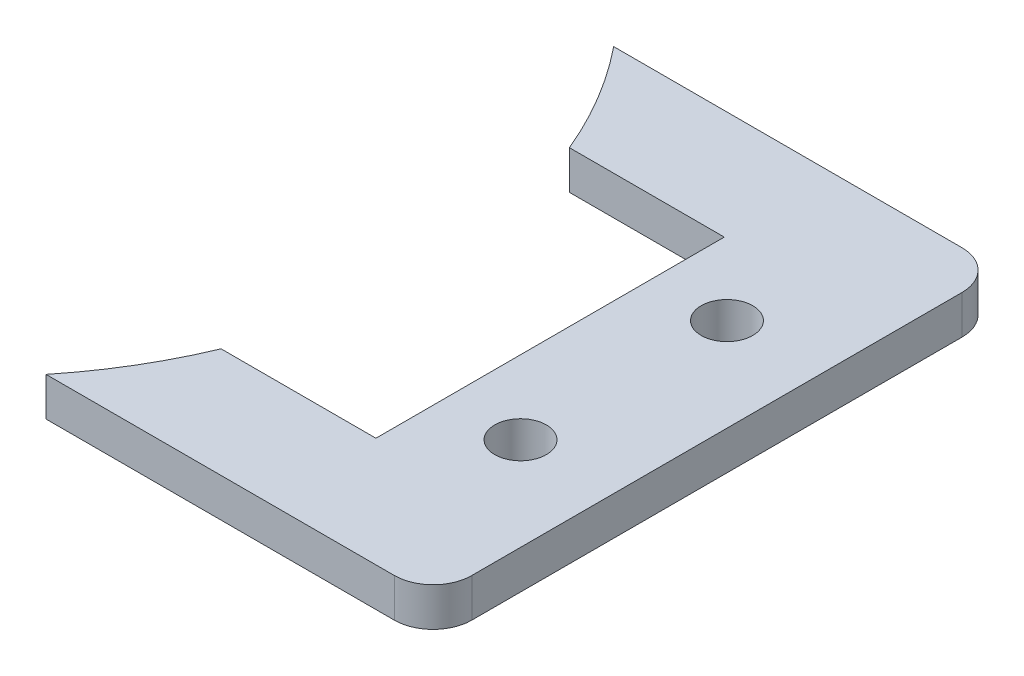
SolidWorks part; units mm, degrees
material "Thornel Mat VMA"
ref_plane "前视基准面" through (0, 0, 0) normal (0, 0, 1) x (1, 0, 0)
ref_plane "上视基准面" through (0, 0, 0) normal (0, 1, 0) x (1, 0, 0)
ref_plane "右视基准面" through (0, 0, 0) normal (1, 0, 0) x (0, 0, -1)
other "Configuration Table"
sketch "草图1" plane through (0, 0, 0) normal (0, 1, 0) x (1, 0, 0)
  line L0 (0, 0) -> (0, 44.3764) construction
  line L1 (0, 0) -> (53.0848, 0) construction
  line L2 (27.2213, 22) -> (57.2213, 22)
  line L3 (57.2213, 22) -> (57.2213, -22)
  line L4 (27.2213, -22) -> (57.2213, -22)
  line L5 (32.2916, 13.5) -> (44.2916, 13.5)
  line L6 (44.2916, 13.5) -> (44.2916, -13.5)
  line L7 (32.2916, -13.5) -> (44.2916, -13.5)
  circle A0 centre (0, 0) radius 35 construction
  arc A1 (27.2213, -22) -> (27.2213, 22) centre (0, 0) ccw
  circle A2 centre (50, 8) radius 2
  circle A3 centre (50, -8) radius 2
  point P10 (57.2213, 0)
  point P18 (44.2916, 0)
  dimension "D1" = 70
  dimension "D4" = 4
  dimension "D5" = 50
  dimension "D2" = 22
  dimension "D3" = 30
  dimension "D6" = 8
  dimension "D7" = 12
  dimension "D8" = 27
extrude "凸台-拉伸1" add sketch "草图1" along normal blind 3 contours A1 L4 L3 L2 L5 L6 L7 A2 A3
fillet "圆角1" radius 3 2 edges at (57.2213, 1.5, -22) (57.2213, 1.5, 22)
